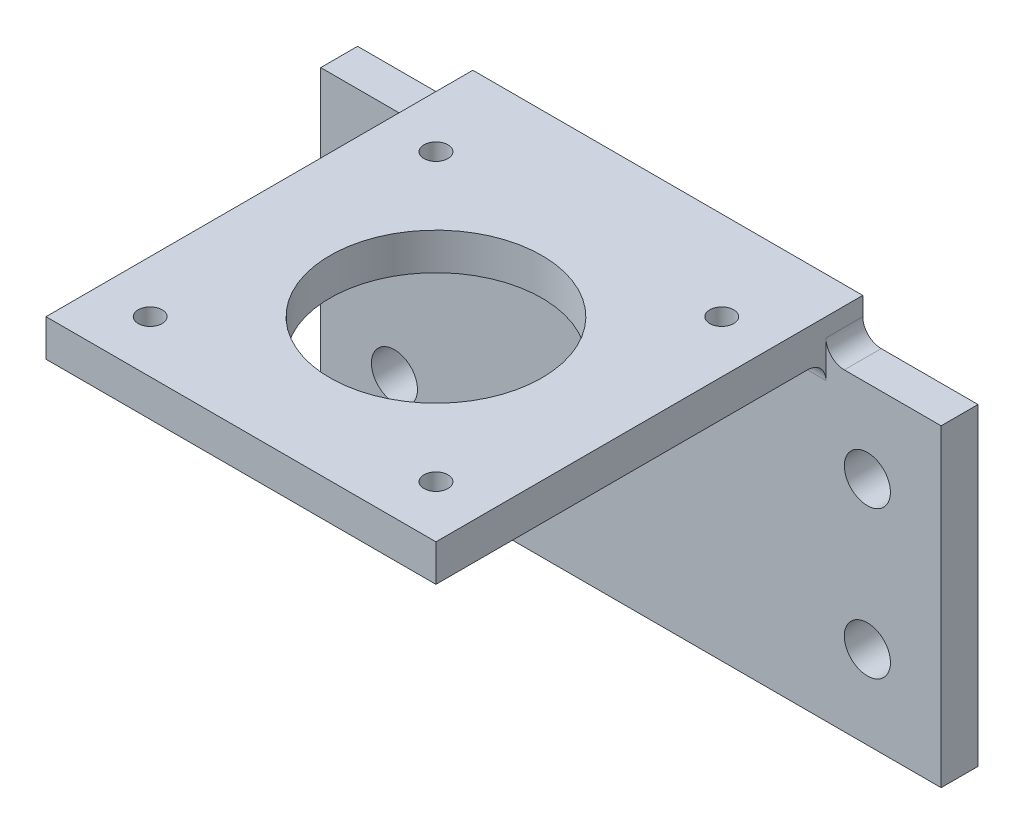
SolidWorks part; units mm, degrees
ref_plane "前视基准面" through (0, 0, 0) normal (0, 0, 1) x (1, 0, 0)
ref_plane "上视基准面" through (0, 0, 0) normal (0, 1, 0) x (1, 0, 0)
ref_plane "右视基准面" through (0, 0, 0) normal (1, 0, 0) x (0, 0, -1)
sketch "草图1" plane through (0, 0, 0) normal (0, 0, 1) x (1, 0, 0)
  line L1 (33.65, -17) -> (-33.65, -17)
  line L2 (33.65, -17) -> (33.65, 17)
  line L3 (33.65, 17) -> (-33.65, 17)
  line L4 (-33.65, -17) -> (-33.65, 17)
  line L5 (33.65, -17) -> (-33.65, 17) construction
  line L6 (33.65, 17) -> (-33.65, -17) construction
  point P0 (0, 0)
  dimension "D1" = 34
  dimension "D2" = 67.3
extrude "凸台-拉伸1" add sketch "草图1" along normal blind 4
sketch "草图2" plane through (0, 0, 4) normal (0, 0, 1) x (1, 0, 0)
  line L0 (0, 17) -> (0, 21)
  line L1 (33.65, 17) -> (-33.65, 17) construction
  line L2 (-21.15, 21) -> (21.15, 21)
  line L3 (21.15, 21) -> (21.15, 17)
  line L4 (21.15, 17) -> (-21.15, 17)
  line L5 (-21.15, 21) -> (-21.15, 17)
  line M6 (33.65, 17) -> (-33.65, 17)
  dimension "D1" = 4
  dimension "D2" = 21.15
extrude "凸台-拉伸2" add sketch "草图2" along normal blind 42.3 separate body contours L2 L5 L0 M6 | L3 L2 L0 M6
sketch "草图3" plane through (0, 0, 4) normal (0, 0, -1) x (-1, 0, 0)
  line L4 (21.15, 21) -> (-21.15, 21)
  line L5 (-21.15, 21) -> (-21.15, 17)
  line L6 (-21.15, 17) -> (21.15, 17)
  line L7 (21.15, 17) -> (21.15, 21)
  line L8 (21.15, 21) -> (-21.15, 21)
  line L9 (-21.15, 21) -> (-21.15, 17)
  line L10 (-21.15, 17) -> (21.15, 17)
  line L11 (21.15, 17) -> (21.15, 21)
  dimension "D1" = 0
extrude "凸台-拉伸3" add sketch "草图3" along normal blind 4
fillet "圆角1" radius 2 1 edges at (0, 17, 4)
fillet "圆角2" radius 2 2 edges at (-21.15, 17, 2) (21.15, 17, 2)
sketch "草图4" plane through (0, 17, 0) normal (0, -1, 0) x (1, 0, 0)
  line L0 (21.15, 46.3) -> (-21.15, 46.3) construction
  line L1 (15.5, 9.65) -> (-15.5, 9.65) construction
  line L2 (15.5, 9.65) -> (15.5, 40.65) construction
  line L3 (15.5, 40.65) -> (-15.5, 40.65) construction
  line L4 (-15.5, 9.65) -> (-15.5, 40.65) construction
  line L5 (15.5, 9.65) -> (-15.5, 40.65) construction
  line L6 (15.5, 40.65) -> (-15.5, 9.65) construction
  line L7 (-21.15, 46.3) -> (-21.15, 6) construction
  circle A0 centre (-15.5, 40.65) radius 1.3
  circle A1 centre (15.5, 40.65) radius 1.3
  circle A2 centre (-15.5, 9.65) radius 1.3
  circle A3 centre (15.5, 9.65) radius 1.3
  circle A4 centre (0, 25.15) radius 11.5
  point P0 (0, 25.15)
  dimension "D5" = 2.6
  dimension "D6" = 2.6
  dimension "D7" = 2.6
  dimension "D8" = 2.6
  dimension "D9" = 23
  dimension "D1" = 5.65
  dimension "D2" = 5.65
  dimension "D3" = 31
  dimension "D4" = 31
extrude "切除-拉伸1" cut sketch "草图4" against normal blind 4
sketch "草图5" plane through (0, 0, 4) normal (0, 0, 1) x (1, 0, 0)
  line L0 (-33.65, 0) -> (-25.65, 0) construction
  line L1 (-33.65, 17) -> (-33.65, -17) construction
  line L2 (-25.65, 0) -> (-25.65, 8) construction
  line L3 (0, -17) -> (0, -9.1113) construction
  line L4 (-33.65, -17) -> (33.65, -17) construction
  line L5 (33.65, 0) -> (25.65, 0) construction
  circle A0 centre (-25.65, 8) radius 2.5
  circle A1 centre (-25.65, -8) radius 2.5
  circle A2 centre (25.65, 8) radius 2.5
  circle A3 centre (25.65, -8) radius 2.5
  dimension "D3" = 5
  dimension "D1" = 8
  dimension "D2" = 8
extrude "切除-拉伸2" cut sketch "草图5" against normal blind 4
